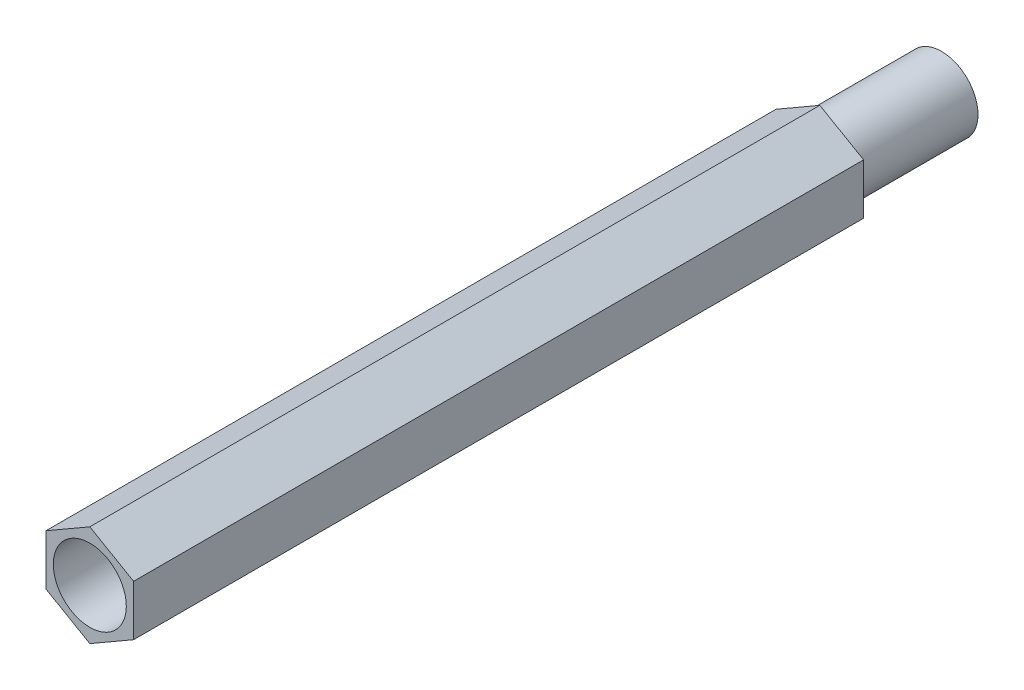
SolidWorks part; units mm, degrees
ref_plane "前视基准面" through (0, 0, 0) normal (0, 0, 1) x (1, 0, 0)
ref_plane "上视基准面" through (0, 0, 0) normal (0, 1, 0) x (1, 0, 0)
ref_plane "右视基准面" through (0, 0, 0) normal (1, 0, 0) x (0, 0, -1)
sketch "草图1" plane through (0, 0, 0) normal (0, 0, 1) x (1, 0, 0)
  line L1 (0, 2.0785) -> (-1.8, 1.0392)
  line L2 (-1.8, 1.0392) -> (-1.8, -1.0392)
  line L3 (-1.8, -1.0392) -> (0, -2.0785)
  line L4 (0, -2.0785) -> (1.8, -1.0392)
  line L5 (1.8, -1.0392) -> (1.8, 1.0392)
  line L6 (1.8, 1.0392) -> (0, 2.0785)
  circle A0 centre (0, 0) radius 1.8 construction
  circle A1 centre (0, 0) radius 1.5
extrude "凸台-拉伸1" add sketch "草图1" along normal blind 30
sketch "草图2" plane through (0, 0, 0) normal (0, 0, -1) x (-1, 0, 0)
  circle A0 centre (0, 0) radius 1.5
extrude "凸台-拉伸2" add sketch "草图2" along normal mid plane 10 contours A0
